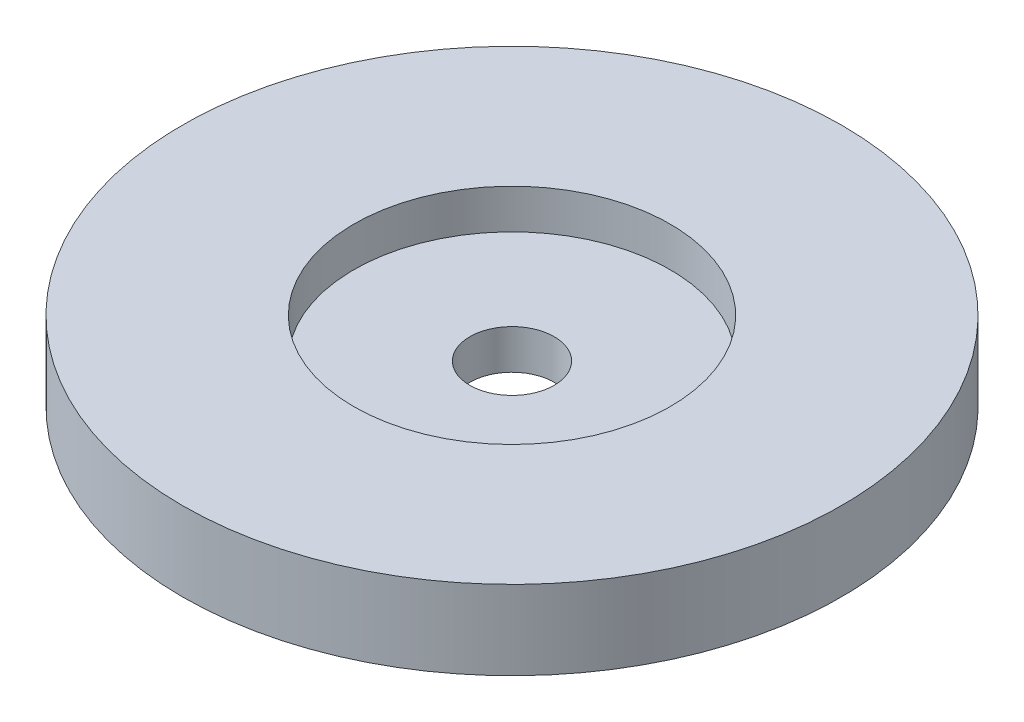
SolidWorks part; units mm, degrees
ref_plane "前视基准面" through (0, 0, 0) normal (0, 0, 1) x (1, 0, 0)
ref_plane "上视基准面" through (0, 0, 0) normal (0, 1, 0) x (1, 0, 0)
ref_plane "右视基准面" through (0, 0, 0) normal (1, 0, 0) x (0, 0, -1)
sketch "草图1" plane through (0, 0, 0) normal (0, 1, 0) x (1, 0, 0)
  circle A0 centre (0, 0) radius 12.5
  dimension "D1" = 25
extrude "凸台-拉伸1" add sketch "草图1" along normal blind 3
sketch "草图2" plane through (0, 3, 0) normal (0, 1, 0) x (1, 0, 0)
  circle A0 centre (0, 0) radius 6
  dimension "D1" = 12
extrude "切除-拉伸1" cut sketch "草图2" against normal blind 1.5
sketch "草图3" plane through (0, 1.5, 0) normal (0, 1, 0) x (1, 0, 0)
  circle A0 centre (0, 0) radius 1.6
  dimension "D1" = 3.2
extrude "切除-拉伸2" cut sketch "草图3" against normal through all
